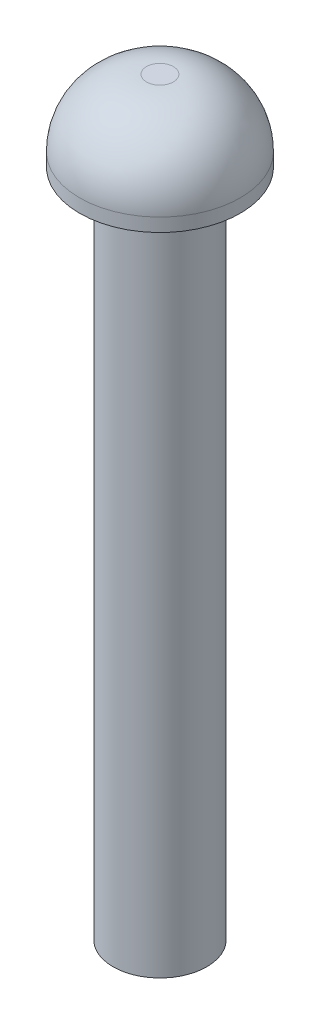
SolidWorks part; units mm, degrees
ref_plane "Alzado" through (0, 0, 0) normal (0, 0, 1) x (1, 0, 0)
ref_plane "Planta" through (0, 0, 0) normal (0, 1, 0) x (1, 0, 0)
ref_plane "Vista lateral" through (0, 0, 0) normal (1, 0, 0) x (0, 0, -1)
sketch "Croquis1" plane through (0, 0, 0) normal (0, 1, 0) x (1, 0, 0)
  circle A0 centre (0, 0) radius 1.75
  dimension "D1" = 3.5
extrude "Saliente-Extruir1" add sketch "Croquis1" along normal blind 25
sketch "Croquis2" plane through (0, 25, 0) normal (0, 1, 0) x (1, 0, 0)
  circle A0 centre (0, 0) radius 3
  dimension "D1" = 6
extrude "Saliente-Extruir2" add sketch "Croquis2" along normal blind 3
fillet "Redondeo1" radius 2.5 1 edges at (0, 28, 3)
